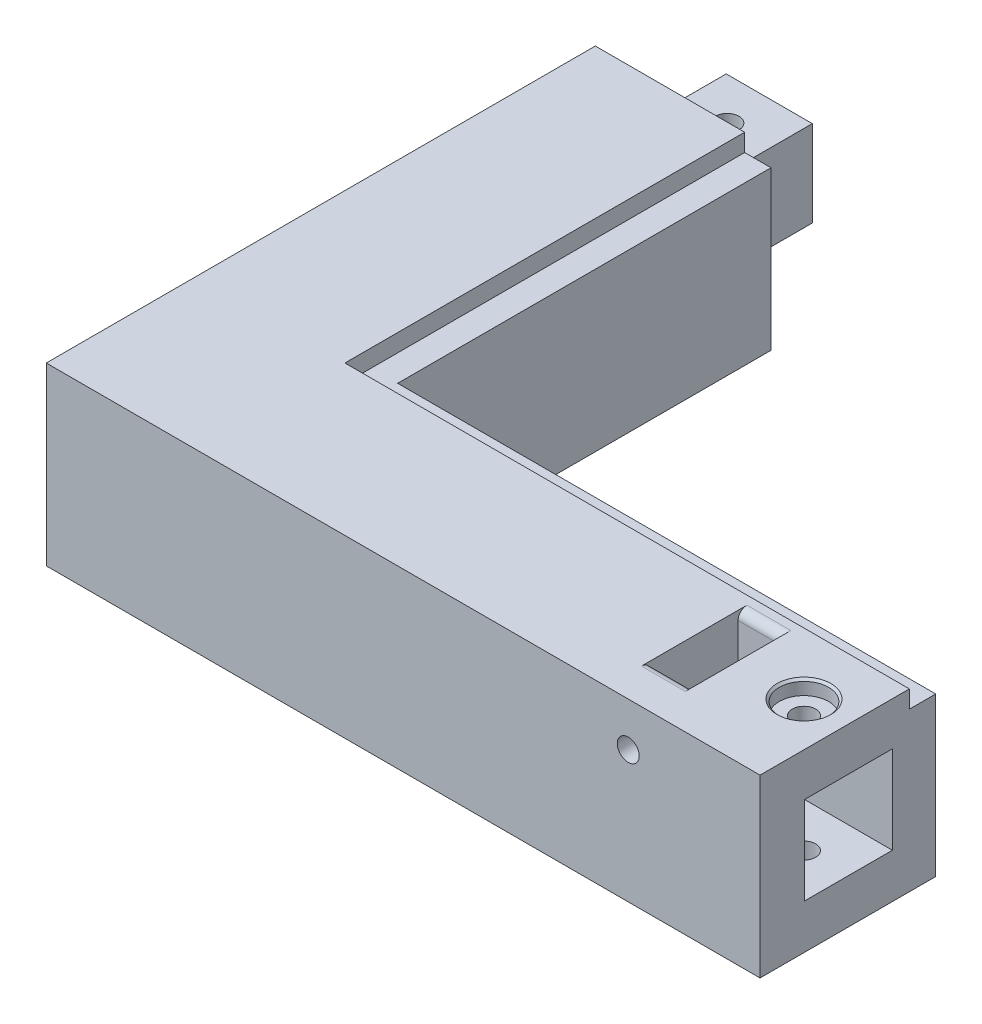
SolidWorks part; units mm, degrees
ref_plane "Front Plane" through (0, 0, 0) normal (0, 0, 1) x (1, 0, 0)
ref_plane "Top Plane" through (0, 0, 0) normal (0, 1, 0) x (1, 0, 0)
ref_plane "Right Plane" through (0, 0, 0) normal (1, 0, 0) x (0, 0, -1)
sketch "Sketch2" plane through (0, 0, 0) normal (0, 1, 0) x (1, 0, 0)
  line L0 (-50.8, 107.95) -> (0, 107.95)
  line L1 (0, 0) -> (155.575, 0)
  line L2 (0, 0) -> (0, 107.95)
  line L5 (-50.8, -50.8) -> (155.575, -50.8)
  line L6 (-50.8, -50.8) -> (-50.8, 107.95)
  line L11 (155.575, 0) -> (155.575, -50.8)
  point P5 (-50.8, -50.8)
  dimension "D1" = 158.75
  dimension "D2" = 50.8
  dimension "D3" = 50.8
  dimension "D4" = 206.375
extrude "Boss-Extrude1" add sketch "Sketch2" along normal blind 50.8
sketch "Sketch3" plane through (155.575, 0, 0) normal (1, 0, 0) x (0, 0, -1)
  line L1 (-37.9399, 12.8601) -> (-12.5399, 12.8601)
  line L2 (-37.9399, 12.8601) -> (-37.9399, 38.2601)
  line L3 (-37.9399, 38.2601) -> (-12.5399, 38.2601)
  line L4 (-12.5399, 12.8601) -> (-12.5399, 38.2601)
  line L5 (-37.9399, 12.8601) -> (-12.5399, 38.2601) construction
  line L6 (-37.9399, 38.2601) -> (-12.5399, 12.8601) construction
  point P0 (-25.2399, 25.5601)
  dimension "D1" = 25.4
extrude "Cut-Extrude1" cut sketch "Sketch3" against normal blind 25.4
sketch "Sketch6" plane through (0, 50.8, 0) normal (0, 1, 0) x (1, 0, 0)
  line L0 (155.575, 0) -> (0, 0) construction
  line L1 (155.575, -50.8) -> (155.575, 0) construction
  point P0 (142.875, -25.4)
  dimension "D1" = 25.4
  dimension "D2" = 12.7
hole_wizard "CBORE for 1/4 Binding Head Machine Screw1" positions "Sketch6" profile "Sketch7" counterbore size "1/4" standard "ANSI Inch" end condition through all
sketch "Sketch7" plane through (142.875, 50.8, 25.4) normal (1, 0, 0) x (0, 0, 1)
  line L0 (0, 0) -> (0, 50.8)
  line L1 (0, 50.8) -> (3.3782, 50.8)
  line L3 (3.3782, 50.8) -> (3.3782, 4.191)
  line L4 (7.1437, 4.191) -> (3.3782, 4.191)
  line L5 (7.1437, 4.191) -> (7.1437, 0.635)
  line L6 (7.1437, 0.635) -> (7.7788, 0)
  line L7 (7.7788, 0) -> (0, 0)
  line L8 (-7.1437, 0.635) -> (-7.7788, 0) construction
  line L11 (0, -6.35) -> (0, 107.95) construction
  dimension "Thru Hole Dia." = 6.7564
  dimension "Thru Hole Depth" = 50.8
  dimension "C'Bore Dia." = 14.2875
  dimension "C'Bore Depth" = 4.191
  dimension "Near C'Sink Dia." = 15.5575
  dimension "Near C'Sink Angle" = 90
sketch "Sketch8" plane through (0, 0, -107.95) normal (0, 0, -1) x (-1, 0, 0)
  line L0 (0, 50.8) -> (0, 0) construction
  line L1 (12.954, 12.954) -> (37.846, 12.954)
  line L2 (12.954, 12.954) -> (12.954, 37.846)
  line L3 (12.954, 37.846) -> (37.846, 37.846)
  line L4 (37.846, 12.954) -> (37.846, 37.846)
  line L5 (12.954, 12.954) -> (37.846, 37.846) construction
  line L6 (12.954, 37.846) -> (37.846, 12.954) construction
  line L8 (0, 50.8) -> (50.8, 50.8) construction
  point P0 (25.4, 25.4)
  dimension "D1" = 24.892
  dimension "D2" = 25.4
  dimension "D3" = 25.4
extrude "Boss-Extrude2" add sketch "Sketch8" along normal blind 24.892
sketch "Sketch12" plane through (0, 37.846, 0) normal (0, 1, 0) x (1, 0, 0)
  line L1 (-37.846, 132.842) -> (-37.846, 107.95) construction
  line L2 (0, 107.95) -> (-50.8, 107.95) construction
  circle A0 centre (-25.4, 120.65) radius 3.429
  point P2 (0, 0)
  dimension "D1" = 6.858
  dimension "D2" = 12.7
  dimension "D3" = 12.446
extrude "Cut-Extrude2" cut sketch "Sketch12" against normal blind 25.4
sketch "Sketch13" plane through (0, 50.8, 0) normal (0, 1, 0) x (1, 0, 0)
  line L0 (-50.8, 107.95) -> (-50.8, -50.8) construction
  line L1 (-38.1, 63.5) -> (-12.7, 63.5)
  line L2 (-38.1, 63.5) -> (-38.1, 76.2)
  line L3 (-38.1, 76.2) -> (-12.7, 76.2)
  line L4 (-12.7, 63.5) -> (-12.7, 76.2)
  line L5 (-38.1, 63.5) -> (-12.7, 76.2) construction
  line L6 (-38.1, 76.2) -> (-12.7, 63.5) construction
  line L7 (111.125, -12.7) -> (123.825, -12.7)
  line L8 (111.125, -12.7) -> (111.125, -38.1)
  line L9 (111.125, -38.1) -> (123.825, -38.1)
  line L10 (123.825, -12.7) -> (123.825, -38.1)
  line L11 (111.125, -12.7) -> (123.825, -38.1) construction
  line L12 (111.125, -38.1) -> (123.825, -12.7) construction
  line L14 (155.575, 0) -> (0, 0) construction
  line L16 (0, 107.95) -> (-50.8, 107.95) construction
  line L17 (155.575, -50.8) -> (155.575, 0) construction
  point P0 (-25.4, 69.85)
  point P5 (117.475, -25.4)
  dimension "D1" = 25.4
  dimension "D2" = 12.7
  dimension "D3" = 12.7
  dimension "D4" = 38.1
  dimension "D5" = 25.4
  dimension "D6" = 12.7
  dimension "D7" = 12.7
  dimension "D8" = 38.1
extrude "Cut-Extrude3" cut sketch "Sketch13" against normal blind 25.908 contours L7 L10 L9 L8
fillet "Fillet1" radius 2.54 2 edges at (117.475, 50.8, 38.1) (117.475, 50.8, 12.7)
sketch "Sketch14" plane through (-50.8, 0, 0) normal (-1, 0, 0) x (0, 0, 1)
  line L0 (-107.95, 50.8) -> (-107.95, 0) construction
  line L1 (-107.95, 50.8) -> (50.8, 50.8) construction
  circle A0 centre (-69.85, 38.1) radius 3.175
  dimension "D1" = 6.35
  dimension "D2" = 38.1
  dimension "D3" = 12.7
sketch "Sketch15" plane through (0, 0, 50.8) normal (0, 0, 1) x (1, 0, 0)
  line L0 (-50.8, 50.8) -> (155.575, 50.8) construction
  line L1 (155.575, 50.8) -> (155.575, 0) construction
  circle A0 centre (117.475, 38.1) radius 3.175
  dimension "D1" = 6.35
  dimension "D2" = 12.7
  dimension "D3" = 38.1
sketch "Sketch17" plane through (0, 50.8, 0) normal (0, 1, 0) x (1, 0, 0)
  line L0 (0, 107.95) -> (0, 0)
  line L1 (0, 0) -> (155.575, 0)
  line L2 (155.575, 0) -> (155.575, -7.62)
  line L3 (155.575, -50.8) -> (155.575, 0) construction
  line L4 (155.575, -7.62) -> (-7.62, -7.62)
  line L5 (-7.62, -7.62) -> (-7.62, 107.95)
  line L6 (0, 107.95) -> (-50.8, 107.95) construction
  line L7 (-7.62, 107.95) -> (0, 107.95)
  dimension "D1" = 7.62
  dimension "D2" = 7.62
extrude "Cut-Extrude6" cut sketch "Sketch17" against normal blind 5.08
extrude "Cut-Extrude7" cut sketch "Sketch15" against normal through all
